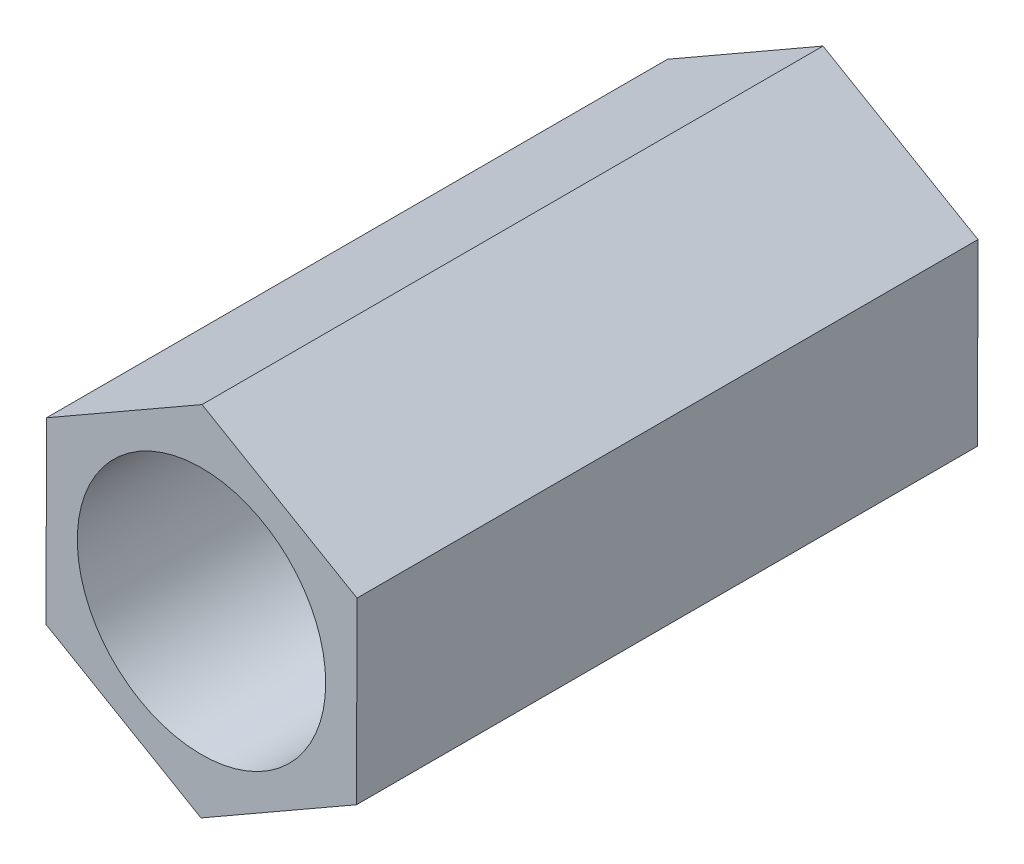
SolidWorks part; units mm, degrees
ref_plane "Płaszczyzna przednia" through (0, 0, 0) normal (0, 0, 1) x (1, 0, 0)
ref_plane "Płaszczyzna górna" through (0, 0, 0) normal (0, 1, 0) x (1, 0, 0)
ref_plane "Płaszczyzna prawa" through (0, 0, 0) normal (1, 0, 0) x (0, 0, -1)
sketch "Sketch1" plane through (0, 0, 0) normal (0, 0, 1) x (1, 0, 0)
  line L1 (2.5042, 1.436) -> (0.0085, 2.8867)
  line L2 (0.0085, 2.8867) -> (-2.4958, 1.4507)
  line L3 (-2.4958, 1.4507) -> (-2.5042, -1.436)
  line L4 (-2.5042, -1.436) -> (-0.0085, -2.8867)
  line L5 (-0.0085, -2.8867) -> (2.4958, -1.4507)
  line L6 (2.4958, -1.4507) -> (2.5042, 1.436)
  circle A0 centre (0, 0) radius 2.5 construction
  point P1 (2.5, -1.436)
  dimension "D1" = 5
extrude "Boss-Extrude1" add sketch "Sketch1" along normal blind 10
hole_wizard "Ø4.0mm Dowel Hole1" positions "Sketch2" profile "Sketch3" hole size "Ø4.0" standard "ANSI Metric" end condition through all
sketch "Sketch2" plane through (0, 0, 10) normal (0, 0, 1) x (1, 0, 0)
  point P0 (0, 0)
sketch "Sketch3" plane through (0, 0, 10) normal (1, 0, 0) x (0, -1, 0)
  line L0 (0, 0) -> (0, 10)
  line L1 (0, 10) -> (2, 10)
  line L2 (2, 10) -> (2, 0)
  line L5 (2, 0) -> (0, 0)
  line L11 (0, -6.35) -> (0, 107.95) construction
  dimension "Thru Hole Dia." = 4
  dimension "Thru Hole Depth" = 10
